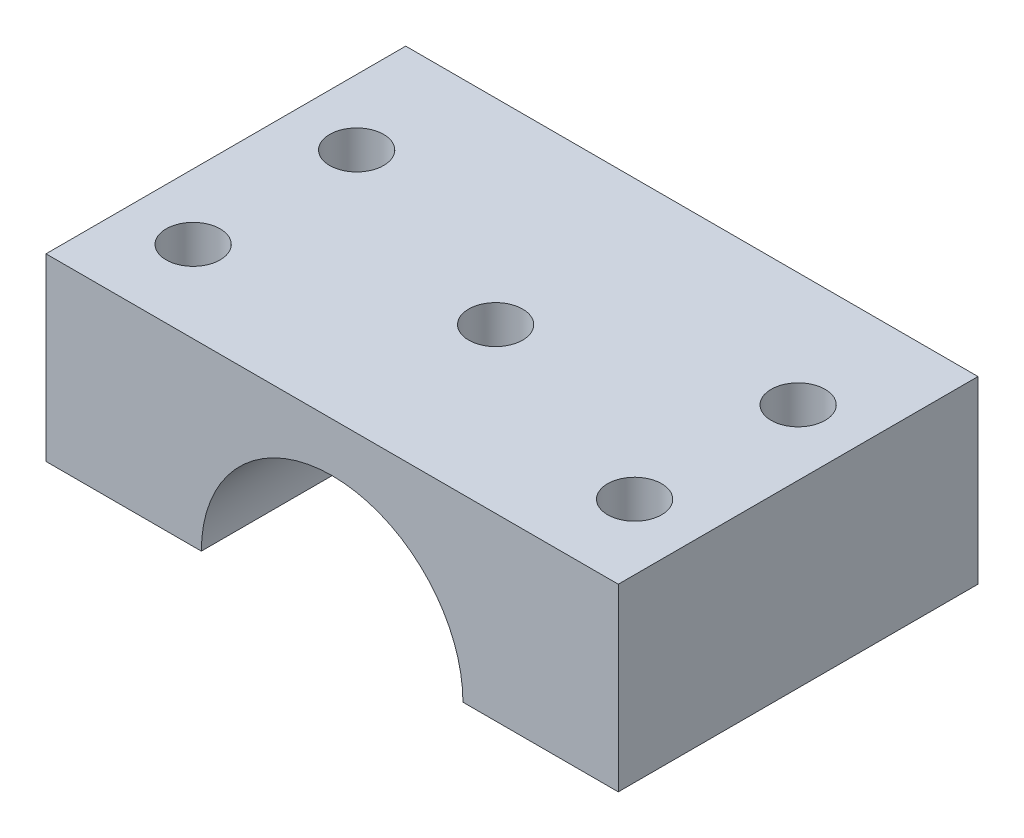
SolidWorks part; units mm, degrees
ref_plane "前视基准面" through (0, 0, 0) normal (0, 0, 1) x (1, 0, 0)
ref_plane "上视基准面" through (0, 0, 0) normal (0, 1, 0) x (1, 0, 0)
ref_plane "右视基准面" through (0, 0, 0) normal (1, 0, 0) x (0, 0, -1)
sketch "草图1" plane through (0, 0, 0) normal (0, 0, 1) x (1, 0, 0)
  line L0 (-17.5, 3) -> (-17.5, 11)
  line L5 (0, 0) -> (0, -11)
  line L6 (-17.5, 11) -> (17.5, 11)
  line L7 (17.5, 11) -> (17.5, 3)
  line L8 (-17.5, 0) -> (17.5, 0)
  line L9 (-17.5, 0) -> (-17.5, 3)
  line L10 (-17.5, 3) -> (17.5, 3)
  line L11 (17.5, 0) -> (17.5, 3)
  line L12 (-17.5, 0) -> (17.5, 3) construction
  line L13 (-17.5, 3) -> (17.5, 0) construction
  line L14 (-11, 0) -> (11, 0)
  circle A0 centre (0, 0) radius 8
  circle A1 centre (0, 0) radius 11
  point P3 (0, 1.5)
  dimension "D1" = 16
  dimension "D2" = 22
  dimension "D3" = 0
  dimension "D7" = 3
extrude "凸台-拉伸1" add sketch "草图1" along normal blind 22 contours A1 L10 L9 L8 | L10 A1 L8 A0 | L10 A1 A0 | A1 L8 L11 L10 | L14 A1 L10 A0 | A1 L6 L0 L10 | A1 L10 L7 L6
sketch "草图3" plane through (0, 0, 0) normal (0, 1, 0) x (1, 0, 0)
  line L0 (-17.5, -22) -> (17.5, -22) construction
  line L3 (17.5, -22) -> (17.5, 0) construction
  circle A0 centre (0, -12) radius 1.65
  dimension "D1" = 3.3
  dimension "D2" = 10
  dimension "D3" = 17.5
extrude "切除-拉伸2" cut sketch "草图3" along normal blind 19 contours A0
sketch "草图4" plane through (0, 0, 0) normal (0, 0, -1) x (-1, 0, 0)
  line L1 (-17.5, 0) -> (17.5, 0)
  line L2 (-17.5, 0) -> (-17.5, 3)
  line L3 (-17.5, 3) -> (17.5, 3)
  line L4 (17.5, 0) -> (17.5, 3)
  circle A0 centre (0, 0) radius 11
extrude "凸台-拉伸2" add sketch "草图4" against normal blind 2
sketch "草图5" plane through (0, 0, 0) normal (0, -1, 0) x (1, 0, 0)
  line L0 (-17.5, 22) -> (-17.5, 0) construction
  line L1 (17.5, 22) -> (17.5, 0) construction
  line L2 (-17.5, 22) -> (-8, 22) construction
  line L3 (8, 22) -> (17.5, 22) construction
  circle A0 centre (-13.5, 17) radius 1.65
  circle A1 centre (-13.5, 7) radius 1.65
  circle A2 centre (13.5, 17) radius 1.65
  circle A3 centre (13.5, 7) radius 1.65
  point P14 (-12.75, 22)
  dimension "D1" = 4
  dimension "D2" = 4
  dimension "D3" = 4
  dimension "D4" = 4
  dimension "D5" = 3.3
  dimension "D6" = 3.3
  dimension "D7" = 3.3
  dimension "D8" = 3.3
  dimension "D9" = 10
  dimension "D10" = 10
  dimension "D11" = 5
  dimension "D12" = 5
extrude "切除-拉伸3" cut sketch "草图5" against normal through all
